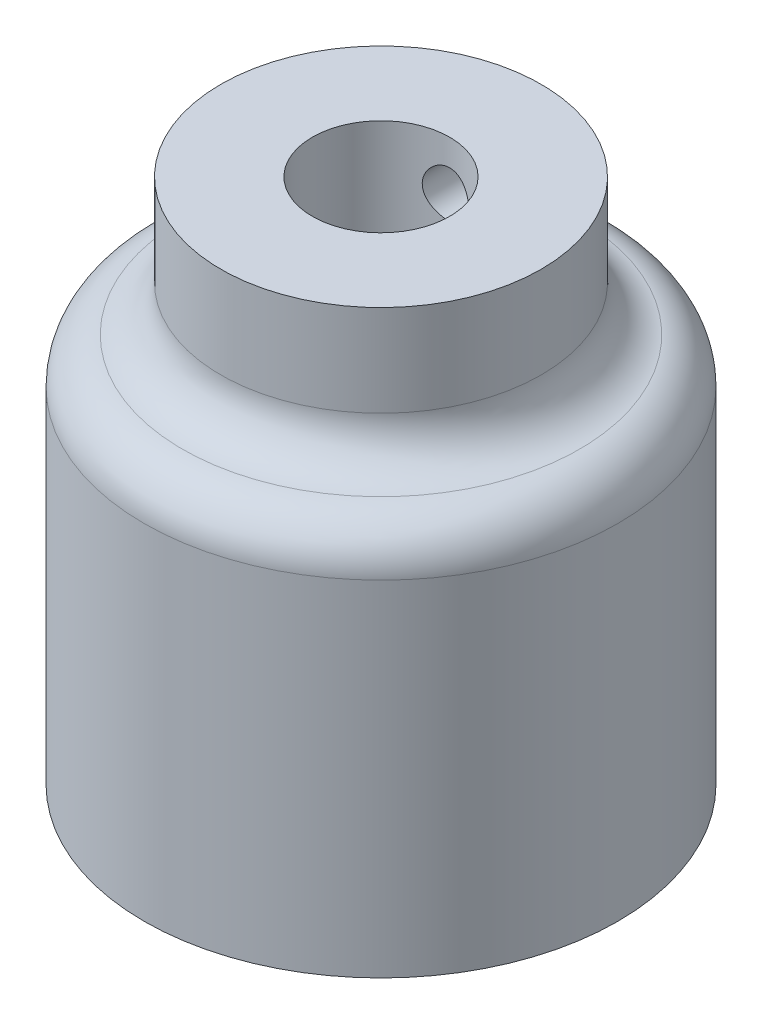
SolidWorks part; units mm, degrees
ref_plane "Front" through (0, 0, 0) normal (0, 0, 1) x (1, 0, 0)
ref_plane "Top" through (0, 0, 0) normal (0, 1, 0) x (1, 0, 0)
ref_plane "Right" through (0, 0, 0) normal (1, 0, 0) x (0, 0, -1)
sketch "Sketch1" plane through (0, 0, 0) normal (0, 0, 1) x (1, 0, 0)
  line L0 (0, 0) -> (3.175, 0)
  line L1 (5.175, -4.6409) -> (5.175, 1.5)
  line L2 (5.175, 1.5) -> (3.5, 1.5)
  line L3 (3.5, 1.5) -> (3.5, 4.5)
  line L4 (3.5, 4.5) -> (1.5, 4.5)
  line L5 (1.5, 4.5) -> (1.5, 1.5)
  line L6 (1.5, 1.5) -> (0, 1.5)
  line L7 (0, 1.5) -> (0, 0)
  line L8 (5.175, -4.6409) -> (5.175, -7)
  line L9 (5.175, -7) -> (3.175, -7)
  line L10 (3.175, -7) -> (3.175, 0)
  point P0 (3.1909, 0)
  dimension "D1" = 1.5
  dimension "D2" = 3.175
  dimension "D3" = 1.5
  dimension "D4" = 2
  dimension "D5" = 2
  dimension "D6" = 7
  dimension "D7" = 3
revolve "Revolve1" add sketch "Sketch1" angle 360 about L7
fillet "Fillet1" radius 1 1 edges at (-3.5, 1.5, 0)
fillet "Fillet2" radius 1 1 edges at (-5.175, 1.5, 0)
sketch "Sketch3" plane through (0, -7, 0) normal (0, -1, 0) x (1, 0, 0)
  line L0 (2.313, -2.175) -> (-2.313, -2.175)
  arc A0 (-2.313, -2.175) -> (2.313, -2.175) centre (0, 0) ccw
  point P7 (0, -3.175)
  dimension "D1" = 1
extrude "Boss-Extrude1" add sketch "Sketch3" against normal up to surface (7 mm away) up to face at (-3.175, 0, 0)
sketch "Sketch2" plane through (0, 0, 0) normal (0, 0, 1) x (1, 0, 0)
  circle A0 centre (0, -3.1689) radius 1.51
  circle A1 centre (0, 3.41) radius 0.51
  dimension "D1" = 3.02
  dimension "D2" = 1.02
extrude "Cut-Extrude1" cut sketch "Sketch2" against normal up to surface (4.9498 mm away)
sketch "Sketch4" plane through (0, 0, 0) normal (0, -1, 0) x (1, 0, 0)
  circle A0 centre (0, 0) radius 0.75
  dimension "D1" = 1.5
extrude "Cut-Extrude2" cut sketch "Sketch4" against normal up to surface (1.5 mm away) up to face at (-1.5, 1.5, 0)
